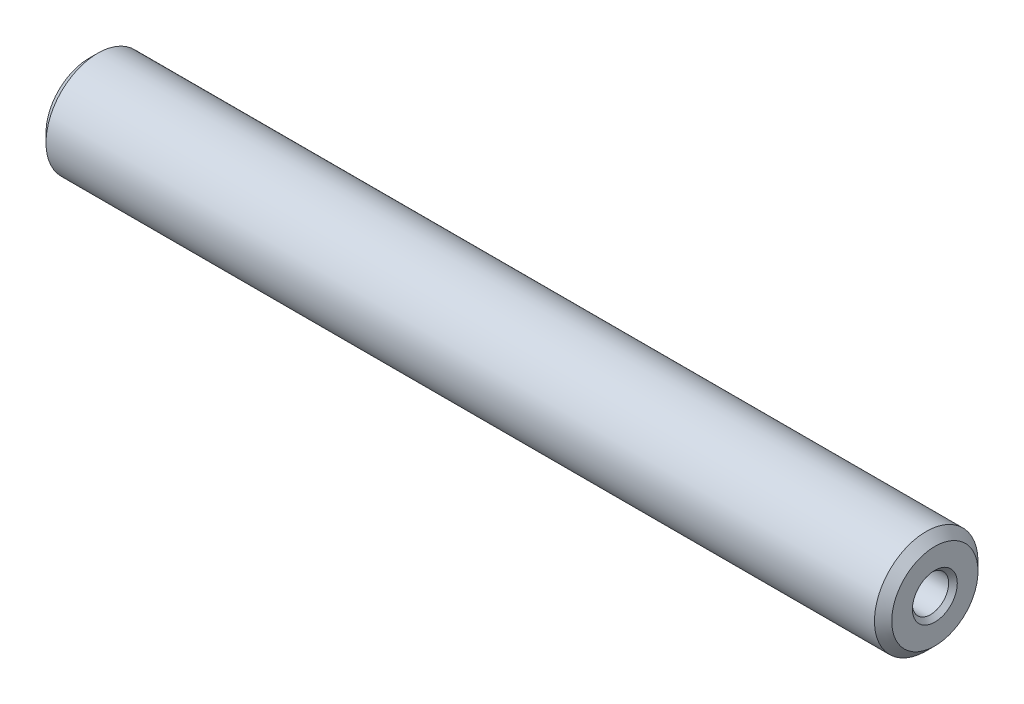
SolidWorks part; units mm, degrees
material "Chrome Stainless Steel"
ref_plane "Front Plane" through (0, 0, 0) normal (0, 0, 1) x (1, 0, 0)
ref_plane "Top Plane" through (0, 0, 0) normal (0, 1, 0) x (1, 0, 0)
ref_plane "Right Plane" through (0, 0, 0) normal (1, 0, 0) x (0, 0, -1)
sketch "Sketch1" plane through (0, 0, 0) normal (1, 0, 0) x (0, 0, -1)
  circle A0 centre (0, 0) radius 6
  dimension "D1" = 12
extrude "Boss-Extrude1" add sketch "Sketch1" along normal blind 98
chamfer "Chamfer1" distance 1 angle 45 2 edges at (98, 0, -6) (0, 0, -6)
hole_wizard "M5 Tapped Hole1" positions "Sketch3" profile "Sketch2" tap size "M5" standard "ISO"
sketch "Sketch3" plane through (98, 0, 0) normal (1, 0, 0) x (0, 0, -1)
  point P1 (0, 0)
sketch "Sketch2" plane through (98, 0, 0) normal (0, 1, 0) x (0, 0, -1)
  line L0 (0, 0) -> (0, 15.2618)
  line L1 (0, 15.2618) -> (2.1, 14)
  line L2 (2.1, 14) -> (2.1, 0)
  line L5 (2.1, 0) -> (0, 0)
  line L10 (0, 15.2618) -> (-2.1, 14) construction
  line L11 (0, -6.35) -> (0, 107.95) construction
  dimension "Tap Drill Dia." = 4.2
  dimension "Tap Drill Depth" = 14
  dimension "Drill Angle" = 118
cosmetic thread "Hole Thread1" parameters "D1"=10, "D2"=5
chamfer "Chamfer2" distance 0.5 angle 45 1 edges at (98, 0, -2.1)
hole_wizard "M5 Tapped Hole2" positions "Sketch5" profile "Sketch4" tap size "M5" standard "ISO"
sketch "Sketch5" plane through (0, 0, 0) normal (-1, 0, 0) x (0, 0, 1)
  point P1 (0, 0)
sketch "Sketch4" plane through (0, 0, 0) normal (0, 1, 0) x (0, 0, 1)
  line L0 (0, 0) -> (0, 15.2618)
  line L1 (0, 15.2618) -> (2.1, 14)
  line L2 (2.1, 14) -> (2.1, 0)
  line L5 (2.1, 0) -> (0, 0)
  line L10 (0, 15.2618) -> (-2.1, 14) construction
  line L11 (0, -6.35) -> (0, 107.95) construction
  dimension "Tap Drill Dia." = 4.2
  dimension "Tap Drill Depth" = 14
  dimension "Drill Angle" = 118
cosmetic thread "Hole Thread2" parameters "D1"=10, "D2"=5
chamfer "Chamfer3" distance 0.5 angle 45 1 edges at (0, 0, 2.1)
